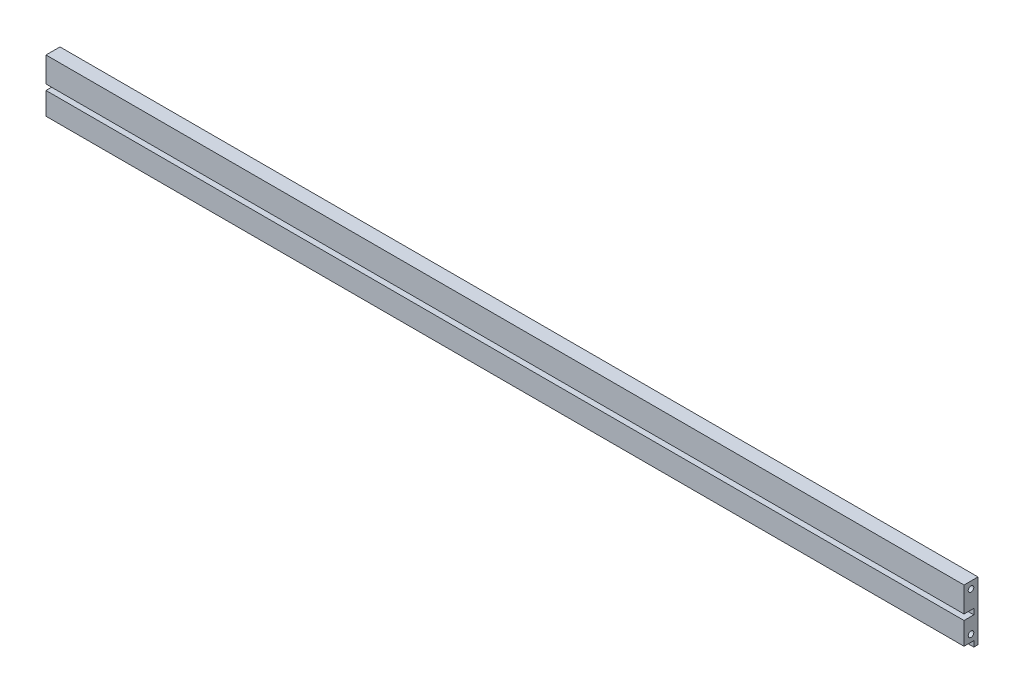
SolidWorks part; units mm, degrees
material "Mahogany"
ref_plane "Front Plane" through (0, 0, 0) normal (0, 0, 1) x (1, 0, 0)
ref_plane "Top Plane" through (0, 0, 0) normal (0, 1, 0) x (1, 0, 0)
ref_plane "Right Plane" through (0, 0, 0) normal (1, 0, 0) x (0, 0, -1)
sketch "Sketch1" plane through (0, 0, 0) normal (0, 0, 1) x (1, 0, 0)
  line L1 (47.3977, 18.5937) -> (-609.6023, 18.5937)
  line L2 (47.3977, 18.5937) -> (47.3977, -23.4063)
  line L3 (47.3977, -23.4063) -> (-609.6023, -23.4063)
  line L4 (-609.6023, 18.5937) -> (-609.6023, -23.4063)
  dimension "D1" = 42
  dimension "D2" = 657
extrude "Boss-Extrude1" add sketch "Sketch1" along normal blind 10
sketch "Sketch2" plane through (0, 0, 10) normal (0, 0, 1) x (1, 0, 0)
  line L0 (-609.6023, 18.5937) -> (-609.6023, -23.4063) construction
  line L1 (-609.6023, -19.4063) -> (47.3977, -19.4063)
  line L2 (-609.6023, -19.4063) -> (-609.6023, -23.4063)
  line L3 (-609.6023, -23.4063) -> (47.3977, -23.4063)
  line L4 (47.3977, -19.4063) -> (47.3977, -23.4063)
  line L5 (47.3977, -23.4063) -> (47.3977, 18.5937) construction
  line L6 (-609.6023, -3.4063) -> (47.3977, -3.4063)
  line L7 (-609.6023, -3.4063) -> (-609.6023, 0.5937)
  line L8 (-609.6023, 0.5937) -> (47.3977, 0.5937)
  line L9 (47.3977, -3.4063) -> (47.3977, 0.5937)
  line L11 (47.3977, 18.5937) -> (-609.6023, 18.5937) construction
  dimension "D1" = 4
  dimension "D2" = 18
  dimension "D3" = 4
extrude "Cut-Extrude1" cut sketch "Sketch2" against normal blind 7
sketch "Sketch3" plane through (-609.6023, 0, 0) normal (-1, 0, 0) x (0, 0, 1)
  line L0 (0, 18.5937) -> (0, -23.4063) construction
  line L2 (10, 18.5937) -> (0, 18.5937) construction
  line L3 (3, -19.4063) -> (10, -19.4063) construction
  circle A0 centre (5, 13.5937) radius 2
  circle A1 centre (5, -14.4063) radius 2
  dimension "D3" = 4
  dimension "D4" = 4
  dimension "D1" = 5
  dimension "D2" = 5
  dimension "D5" = 5
extrude "Cut-Extrude2" cut sketch "Sketch3" against normal blind 10
sketch "Sketch4" plane through (47.3977, 0, 0) normal (1, 0, 0) x (0, 0, -1)
  line L0 (-10, -19.4063) -> (-10, -3.4063) construction
  line L1 (-10, 18.5937) -> (0, 18.5937) construction
  line L2 (-3, -19.4063) -> (-10, -19.4063) construction
  circle A0 centre (-5, 13.5937) radius 2
  circle A1 centre (-5, -14.4063) radius 2
  dimension "D3" = 4
  dimension "D4" = 4
  dimension "D1" = 5
  dimension "D2" = 5
  dimension "D5" = 5
extrude "Cut-Extrude3" cut sketch "Sketch4" against normal blind 10
sketch "Sketch5" plane through (0, -19.4063, 0) normal (0, -1, 0) x (-1, 0, 0)
  line L0 (609.6023, -3) -> (609.6023, -10) construction
  line L1 (609.6023, -3) -> (-47.3977, -3) construction
  line L2 (-47.3977, -3) -> (-47.3977, -10) construction
  circle A0 centre (559.6023, -6.5) radius 1.5
  circle A1 centre (281.1023, -6.5) radius 1.5
  circle A2 centre (2.6023, -6.5) radius 1.5
  dimension "D1" = 3
  dimension "D4" = 3
  dimension "D6" = 3
  dimension "D2" = 50
  dimension "D3" = 3.5
  dimension "D5" = 328.5
  dimension "D7" = 50
extrude "Cut-Extrude4" cut sketch "Sketch5" against normal blind 12
